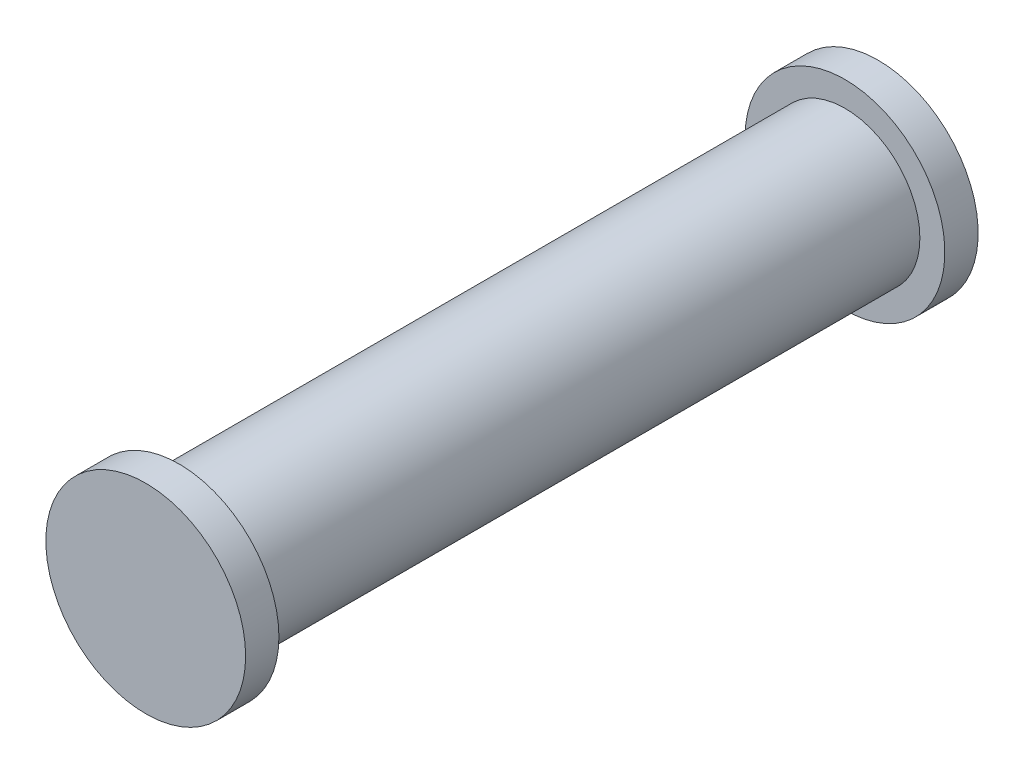
SolidWorks part; units mm, degrees
ref_plane "Ebene vorne" through (0, 0, 0) normal (0, 0, 1) x (1, 0, 0)
ref_plane "Ebene oben" through (0, 0, 0) normal (0, 1, 0) x (1, 0, 0)
ref_plane "Ebene rechts" through (0, 0, 0) normal (1, 0, 0) x (0, 0, -1)
sketch "Skizze1" plane through (0, 0, 0) normal (0, 0, 1) x (1, 0, 0)
  circle A0 centre (-14.9, 25) radius 2.25
  dimension "D1" = 4.5
extrude "Aufsatz-Linear austragen1" add sketch "Skizze1" against normal up to surface (20 mm away)
sketch "Skizze2" plane through (0, 0, 0) normal (0, 0, 1) x (1, 0, 0)
  circle A0 centre (-14.9, 25) radius 3
  dimension "D1" = 6
extrude "Aufsatz-Linear austragen2" add sketch "Skizze2" along normal blind 1
sketch "Skizze3" plane through (0, 0, -20) normal (0, 0, -1) x (-1, 0, 0)
  circle A0 centre (14.9, 25) radius 3
  dimension "D1" = 6
extrude "Aufsatz-Linear austragen3" add sketch "Skizze3" along normal blind 1
